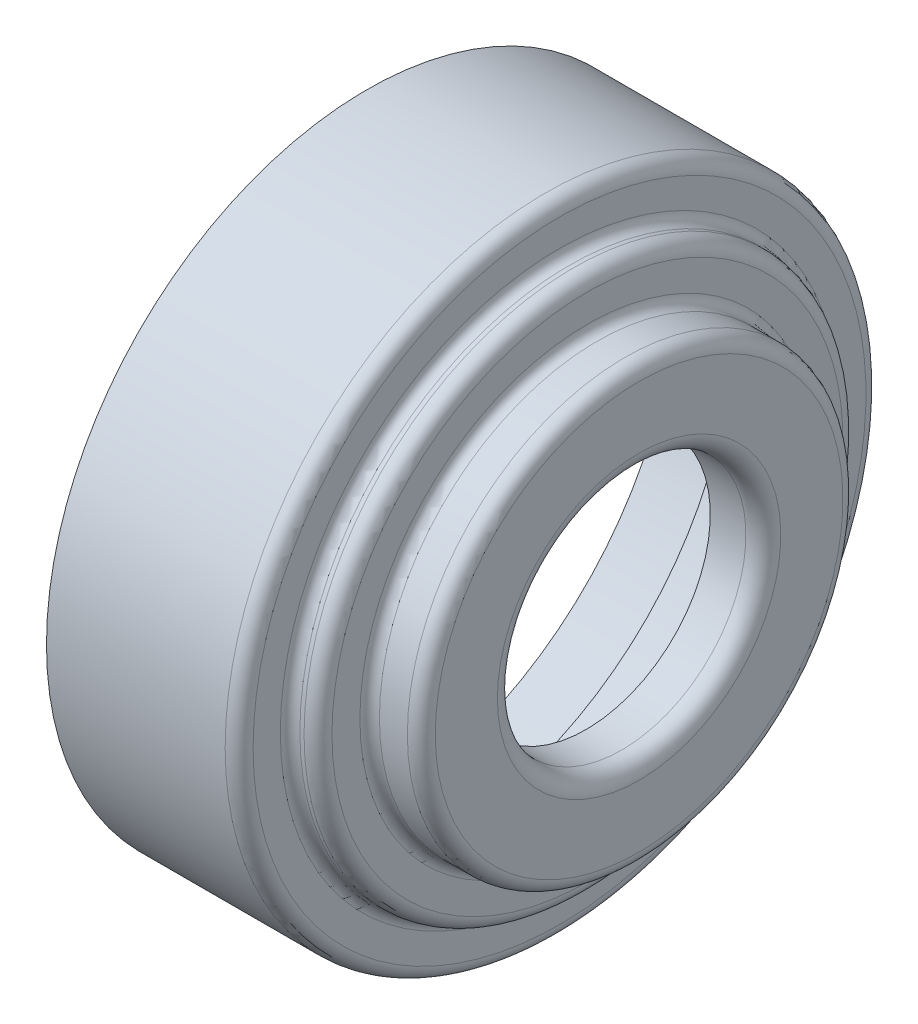
SolidWorks part; units mm, degrees
ref_plane "前视基准面" through (0, 0, 0) normal (0, 0, 1) x (1, 0, 0)
ref_plane "上视基准面" through (0, 0, 0) normal (0, 1, 0) x (1, 0, 0)
ref_plane "右视基准面" through (0, 0, 0) normal (1, 0, 0) x (0, 0, -1)
sketch "草图1" plane through (0, 0, 0) normal (0, 0, 1) x (1, 0, 0)
  line L0 (-35.4342, 0) -> (54.6714, 0) construction
  line L1 (0, 42.5099) -> (0, -37.8665) construction
  line L2 (-7, 21.15) -> (0, 21.15)
  line L3 (0, 21.15) -> (0, 17.8)
  line L4 (0, 17.8) -> (2, 17.8)
  line L5 (2, 17.8) -> (2, 13.6)
  line L6 (2, 13.6) -> (5.7, 13.6)
  line L7 (5.7, 13.6) -> (5.7, 9.55)
  line L8 (5.7, 9.55) -> (3.7, 9.55)
  line L9 (-12, 22.15) -> (-12, 22.95)
  line L10 (-12, 22.95) -> (1.8, 22.95)
  line L11 (1.8, 22.95) -> (1.8, 19.3)
  line L12 (1.8, 19.3) -> (3.8, 19.3)
  line L13 (3.8, 19.3) -> (3.8, 15.6)
  line L14 (3.8, 15.6) -> (7.5, 15.6)
  line L15 (7.5, 15.6) -> (7.5, 8.9)
  line L16 (7.5, 8.9) -> (3.7, 8.9)
  line L17 (3.7, 8.9) -> (3.7, 9.55)
  line L18 (-12, 22.15) -> (-7, 22.15)
  line L19 (-7, 22.15) -> (-7, 21.15)
  dimension "D1" = 19.1
  dimension "D2" = 27.2
  dimension "D3" = 35.6
  dimension "D4" = 42.3
  dimension "D5" = 2
  dimension "D6" = 3.7
  dimension "D7" = 2
  dimension "D8" = 44.3
  dimension "D9" = 45.9
  dimension "D10" = 1.8
  dimension "D11" = 1.8
  dimension "D12" = 38.6
  dimension "D13" = 1.8
  dimension "D14" = 31.2
  dimension "D15" = 1.8
  dimension "D16" = 17.8
  dimension "D17" = 5
  dimension "D18" = 13.8
revolve "旋转1" add sketch "草图1" angle 360 about L0
fillet "圆角1" radius 1.25 1 edges at (7.5, 0, 8.9)
fillet "圆角2" radius 1 3 edges at (3.8, 0, 19.3) (7.5, 0, 15.6) (1.8, 0, 22.95)
fillet "圆角3" radius 0.7 2 edges at (1.8, 0, 19.3) (3.8, 0, 15.6)
fillet "圆角4" radius 0.4 1 edges at (5.7, 0, 9.55)
fillet "圆角5" radius 0.2 1 edges at (5.7, 0, 13.6)
fillet "圆角6" radius 0.6 2 edges at (2, 0, 17.8) (0, 0, 21.15)
fillet "圆角7" radius 2 1 edges at (2, 0, 13.6)
fillet "圆角8" radius 0.2 1 edges at (0, 0, 17.8)
